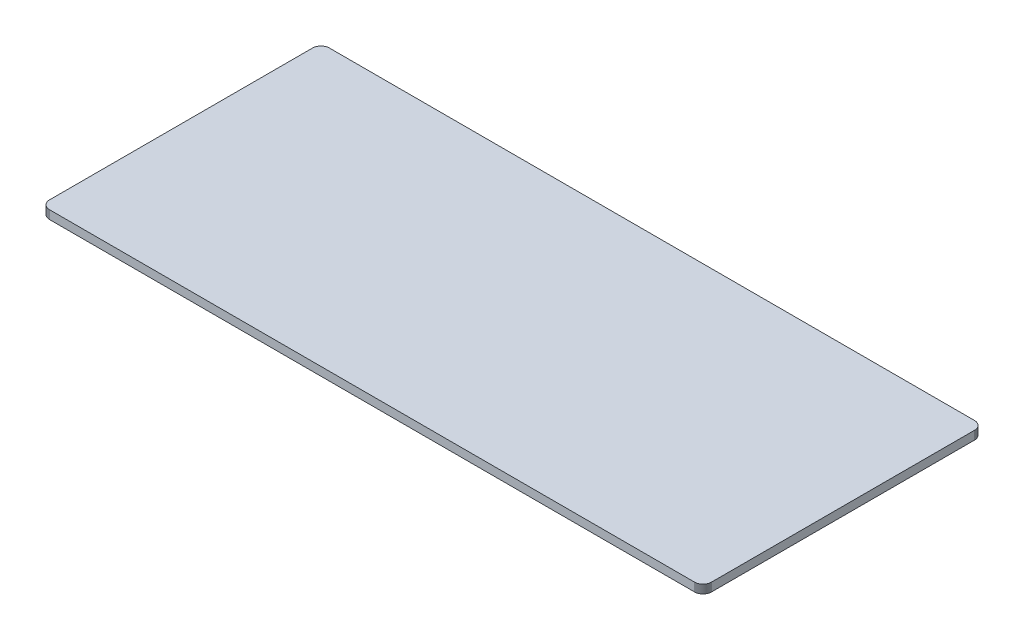
SolidWorks part; units mm, degrees
ref_plane "Front Plane" through (0, 0, 0) normal (0, 0, 1) x (1, 0, 0)
ref_plane "Top Plane" through (0, 0, 0) normal (0, 1, 0) x (1, 0, 0)
ref_plane "Right Plane" through (0, 0, 0) normal (1, 0, 0) x (0, 0, -1)
sketch "Sketch3" plane through (0, 0, 0) normal (0, 1, 0) x (1, 0, 0)
  line L0 (382.958, 164.299) -> (383.35, 164.284)
  line L1 (383.35, 164.284) -> (383.741, 164.237)
  line L2 (383.741, 164.237) -> (384.126, 164.162)
  line L3 (384.126, 164.162) -> (384.503, 164.055)
  line L4 (384.503, 164.055) -> (384.87, 163.919)
  line L5 (384.87, 163.919) -> (385.226, 163.755)
  line L6 (385.226, 163.755) -> (385.572, 163.564)
  line L7 (385.572, 163.564) -> (385.897, 163.344)
  line L8 (385.897, 163.344) -> (386.203, 163.102)
  line L9 (386.203, 163.102) -> (386.493, 162.834)
  line L10 (386.493, 162.834) -> (386.761, 162.547)
  line L11 (386.761, 162.547) -> (387.004, 162.238)
  line L12 (387.004, 162.238) -> (387.223, 161.913)
  line L13 (387.223, 161.913) -> (387.414, 161.569)
  line L14 (387.414, 161.569) -> (387.576, 161.212)
  line L15 (387.576, 161.212) -> (387.713, 160.845)
  line L16 (387.713, 160.845) -> (387.819, 160.467)
  line L17 (387.819, 160.467) -> (387.897, 160.082)
  line L18 (387.897, 160.082) -> (387.943, 159.693)
  line L19 (387.943, 159.693) -> (387.96, 159.299)
  line L20 (387.96, 159.299) -> (387.96, 5.2724)
  line L21 (387.96, 5.2724) -> (387.943, 4.881)
  line L22 (387.943, 4.881) -> (387.897, 4.491)
  line L23 (387.897, 4.491) -> (387.819, 4.1066)
  line L24 (387.819, 4.1066) -> (387.713, 3.7276)
  line L25 (387.713, 3.7276) -> (387.576, 3.3597)
  line L26 (387.576, 3.3597) -> (387.414, 3.0041)
  line L27 (387.414, 3.0041) -> (387.223, 2.661)
  line L28 (387.223, 2.661) -> (387.004, 2.3344)
  line L29 (387.004, 2.3344) -> (386.761, 2.0257)
  line L30 (386.761, 2.0257) -> (386.493, 1.7377)
  line L31 (386.493, 1.7377) -> (386.203, 1.4704)
  line L32 (386.203, 1.4704) -> (385.897, 1.2278)
  line L33 (385.897, 1.2278) -> (385.572, 1.0101)
  line L34 (385.572, 1.0101) -> (385.226, 0.8186)
  line L35 (385.226, 0.8186) -> (384.87, 0.6546)
  line L36 (384.87, 0.6546) -> (384.503, 0.5181)
  line L37 (384.503, 0.5181) -> (384.126, 0.412)
  line L38 (384.126, 0.412) -> (383.741, 0.3349)
  line L39 (383.741, 0.3349) -> (383.35, 0.2894)
  line L40 (383.35, 0.2894) -> (382.958, 0.2729)
  line L41 (382.958, 0.2729) -> (5.096, 0.2729)
  line L42 (5.096, 0.2729) -> (4.7019, 0.2894)
  line L43 (4.7019, 0.2894) -> (4.3119, 0.3349)
  line L44 (4.3119, 0.3349) -> (3.9274, 0.412)
  line L45 (3.9274, 0.412) -> (3.5498, 0.5181)
  line L46 (3.5498, 0.5181) -> (3.1819, 0.6546)
  line L47 (3.1819, 0.6546) -> (2.825, 0.8186)
  line L48 (2.825, 0.8186) -> (2.4819, 1.0101)
  line L49 (2.4819, 1.0101) -> (2.1566, 1.2278)
  line L50 (2.1566, 1.2278) -> (1.848, 1.4704)
  line L51 (1.848, 1.4704) -> (1.5599, 1.7377)
  line L52 (1.5599, 1.7377) -> (1.2926, 2.0257)
  line L53 (1.2926, 2.0257) -> (1.0501, 2.3344)
  line L54 (1.0501, 2.3344) -> (0.831, 2.661)
  line L55 (0.831, 2.661) -> (0.6394, 3.0041)
  line L56 (0.6394, 3.0041) -> (0.4754, 3.3597)
  line L57 (0.4754, 3.3597) -> (0.339, 3.7276)
  line L58 (0.339, 3.7276) -> (0.2329, 4.1066)
  line L59 (0.2329, 4.1066) -> (0.1571, 4.491)
  line L60 (0.1571, 4.491) -> (0.1102, 4.881)
  line L61 (0.1102, 4.881) -> (0.0951, 5.2737)
  line L62 (0.0951, 5.2737) -> (0.0951, 159.299)
  line L63 (0.0951, 159.299) -> (0.1102, 159.693)
  line L64 (0.1102, 159.693) -> (0.1571, 160.082)
  line L65 (0.1571, 160.082) -> (0.2329, 160.467)
  line L66 (0.2329, 160.467) -> (0.339, 160.845)
  line L67 (0.339, 160.845) -> (0.4754, 161.212)
  line L68 (0.4754, 161.212) -> (0.6394, 161.569)
  line L69 (0.6394, 161.569) -> (0.831, 161.913)
  line L70 (0.831, 161.913) -> (1.0501, 162.238)
  line L71 (1.0501, 162.238) -> (1.2926, 162.547)
  line L72 (1.2926, 162.547) -> (1.5599, 162.834)
  line L73 (1.5599, 162.834) -> (1.848, 163.102)
  line L74 (1.848, 163.102) -> (2.1566, 163.344)
  line L75 (2.1566, 163.344) -> (2.4819, 163.564)
  line L76 (2.4819, 163.564) -> (2.825, 163.755)
  line L77 (2.825, 163.755) -> (3.1819, 163.919)
  line L78 (3.1819, 163.919) -> (3.5498, 164.055)
  line L79 (3.5498, 164.055) -> (3.9274, 164.162)
  line L80 (3.9274, 164.162) -> (4.3119, 164.237)
  line L81 (4.3119, 164.237) -> (4.7019, 164.284)
  line L82 (4.7019, 164.284) -> (5.096, 164.299)
  line L83 (5.096, 164.299) -> (382.958, 164.299)
extrude "Boss-Extrude2" add sketch "Sketch3" along normal blind 5
